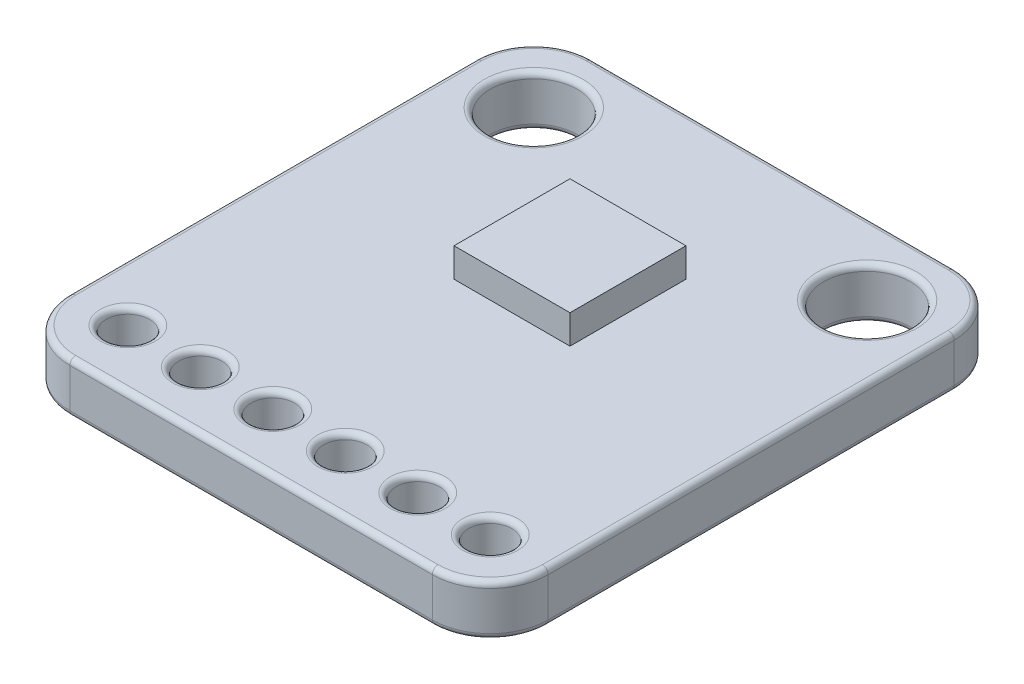
SolidWorks part; units mm, degrees
ref_plane "Alzado" through (0, 0, 0) normal (0, 0, 1) x (1, 0, 0)
ref_plane "Planta" through (0, 0, 0) normal (0, 1, 0) x (1, 0, 0)
ref_plane "Vista lateral" through (0, 0, 0) normal (1, 0, 0) x (0, 0, -1)
sketch "Croquis1" plane through (0, 0, 0) normal (0, 1, 0) x (1, 0, 0)
  line L0 (0, 0) -> (0, 12.3061) construction
  line L1 (-6.25, -9) -> (6.25, -9)
  line L2 (-8.25, -7) -> (-8.25, 7)
  line L3 (-6.25, 9) -> (6.25, 9)
  line L4 (8.25, -7) -> (8.25, 7)
  line L5 (-8.25, -9) -> (8.25, 9) construction
  line L6 (-8.25, 9) -> (8.25, -9) construction
  line L7 (0, 0) -> (15.75, 0) construction
  arc A0 (-6.25, -9) -> (-8.25, -7) centre (-6.25, -7) cw
  arc A1 (6.25, -9) -> (8.25, -7) centre (6.25, -7) ccw
  arc A2 (6.25, 9) -> (8.25, 7) centre (6.25, 7) cw
  arc A3 (-8.25, 7) -> (-6.25, 9) centre (-6.25, 7) cw
  circle A6 centre (6.25, -7) radius 0.75
  circle A7 centre (3.75, -7) radius 0.75
  circle A8 centre (1.25, -7) radius 0.75
  circle A9 centre (-1.25, -7) radius 0.75
  circle A10 centre (-3.75, -7) radius 0.75
  circle A11 centre (-6.25, -7) radius 0.75
  circle A12 centre (-5.75, 6.5) radius 1.5
  circle A13 centre (5.75, 6.5) radius 1.5
  point P0 (0, 0)
  dimension "D3" = 2
  dimension "D4" = 3
  dimension "D5" = 1.5
  dimension "D7" = 2.5
  dimension "D1" = 18
  dimension "D2" = 16.5
  dimension "D8" = 2.5
  dimension "D6" = 6
extrude "Saliente-Extruir1" add sketch "Croquis1" along normal blind 1.75
fillet "Redondeo1" radius 0.2 32 edges at (-6.25, 0, 7.75) (-1.25, 0, 7.75) (3.75, 0, 7.75) (-5.75, 0, -5) (0, 0, 9) (7.6642, 0, 8.4142) (8.25, 0, 0) (7.6642, 0, -8.4142) (0, 0, -9) (-7.6642, 0, -8.4142) (-8.25, 0, 0) (-7.6642, 0, 8.4142) (6.25, 0, 7.75) (1.25, 0, 7.75) (-3.75, 0, 7.75) (-6.25, 1.75, 7.75) (-3.75, 1.75, 7.75) (-1.25, 1.75, 7.75) (1.25, 1.75, 7.75) (3.75, 1.75, 7.75) (6.25, 1.75, 7.75) (-5.75, 1.75, -5) (-8.25, 1.75, 0) (-7.6642, 1.75, -8.4142) (0, 1.75, -9) (7.6642, 1.75, -8.4142) (8.25, 1.75, 0) (7.6642, 1.75, 8.4142) (0, 1.75, 9) (-7.6642, 1.75, 8.4142) (5.75, 0, -8) (5.75, 1.75, -8)
sketch "Croquis2" plane through (0, 1.75, 0) normal (0, 1, 0) x (1, 0, 0)
  line L0 (6.25, 9) -> (-6.25, 9) construction
  line L1 (-2, 0) -> (2, 0)
  line L2 (-2, 0) -> (-2, 4)
  line L3 (-2, 4) -> (2, 4)
  line L4 (2, 0) -> (2, 4)
  line L5 (-8.25, -7) -> (-8.25, 7) construction
  dimension "D1" = 4
  dimension "D2" = 4
  dimension "D3" = 5
  dimension "D4" = 6.25
extrude "Saliente-Extruir2" add sketch "Croquis2" along normal blind 1 contours L2 L1 L4 L3
